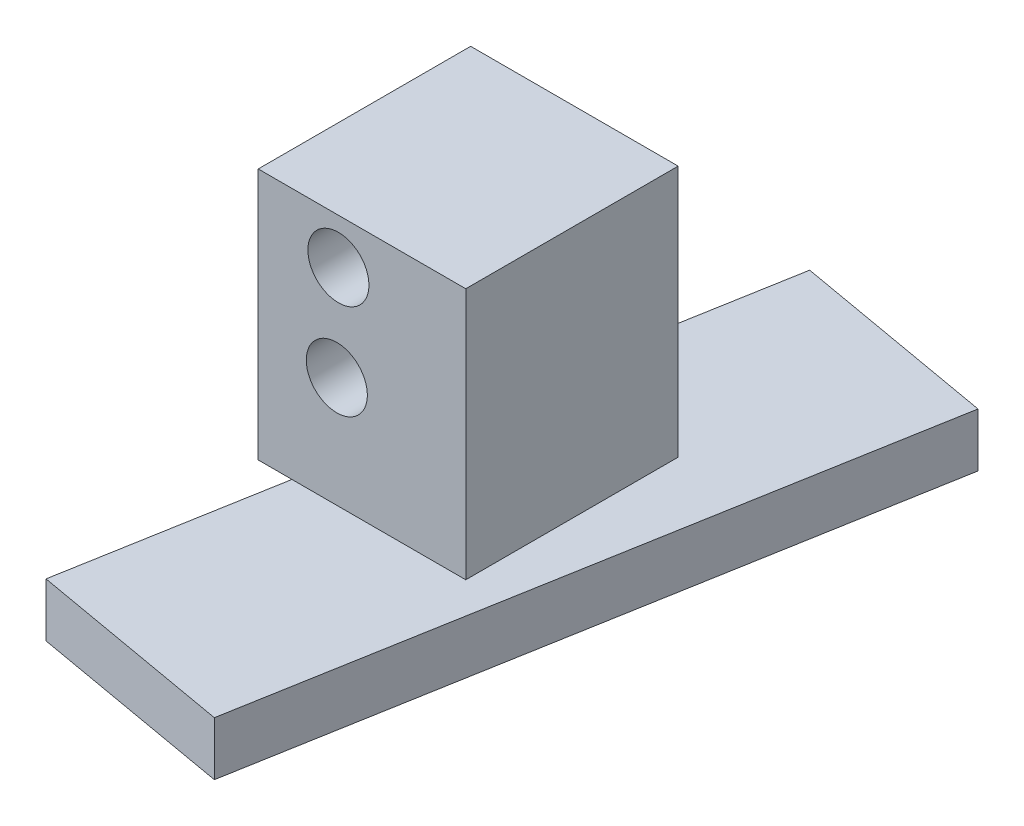
SolidWorks part; units mm, degrees
ref_plane "Front Plane" through (0, 0, 0) normal (0, 0, 1) x (1, 0, 0)
ref_plane "Top Plane" through (0, 0, 0) normal (0, 1, 0) x (1, 0, 0)
ref_plane "Right Plane" through (0, 0, 0) normal (1, 0, 0) x (0, 0, -1)
sketch "Sketch1" plane through (0, 0, 0) normal (0, 0, 1) x (1, 0, 0)
  line L0 (428.9902, 135.2131) -> (450.5802, 135.2131)
  line L1 (417.71, 135.4006) -> (443.5981, 134.9701) construction
  line L2 (450.5802, 135.2131) -> (450.5802, 108.9904)
  line L3 (450.5802, 108.9904) -> (428.9902, 108.9904)
  line L4 (428.9902, 108.9904) -> (428.9902, 135.2131)
  circle A0 centre (437.3311, 130.5) radius 3.175
  circle A1 centre (437.1648, 120.5) radius 3.175
  dimension "D4" = 6.35
  dimension "D5" = 6.35
  dimension "D1" = 3.81
  dimension "D2" = 26.2227
  dimension "D3" = 21.59
extrude "Boss-Extrude1" add sketch "Sketch1" along normal up to surface (22.098 mm away)
ref_plane "Plane1" through (0, 108.9904, 0) normal (0, 1, 0) x (1, 0, 0)
sketch "Sketch2" plane through (0, 108.9904, 0) normal (0, 1, 0) x (1, 0, 0)
  line L0 (428.6627, -43.8503) -> (440.5715, 23.6879)
  line L1 (440.5715, 23.6879) -> (461.8335, 19.9388)
  line L2 (461.8335, 19.9388) -> (449.9247, -47.5993)
  line L3 (449.9247, -47.5993) -> (428.6627, -43.8503)
  line L4 (450.5802, -22.098) -> (428.9902, -22.098) construction
  circle A0 centre (441.2785, -34.4684) radius 3.175
  circle A1 centre (449.2177, 10.557) radius 3.175
  dimension "D6" = 10.795
  dimension "D8" = 6.35
  dimension "D11" = 6.35
  dimension "D1" = 100
  dimension "D2" = 68.58
  dimension "D3" = 7.62
  dimension "D4" = 21.59
  dimension "D5" = 21.59
  dimension "D7" = 11.43
  dimension "D9" = 11.43
  dimension "D10" = 10.795
extrude "Boss-Extrude2" add sketch "Sketch2" against normal blind 5.588 contours L3 L0 L1 L2
